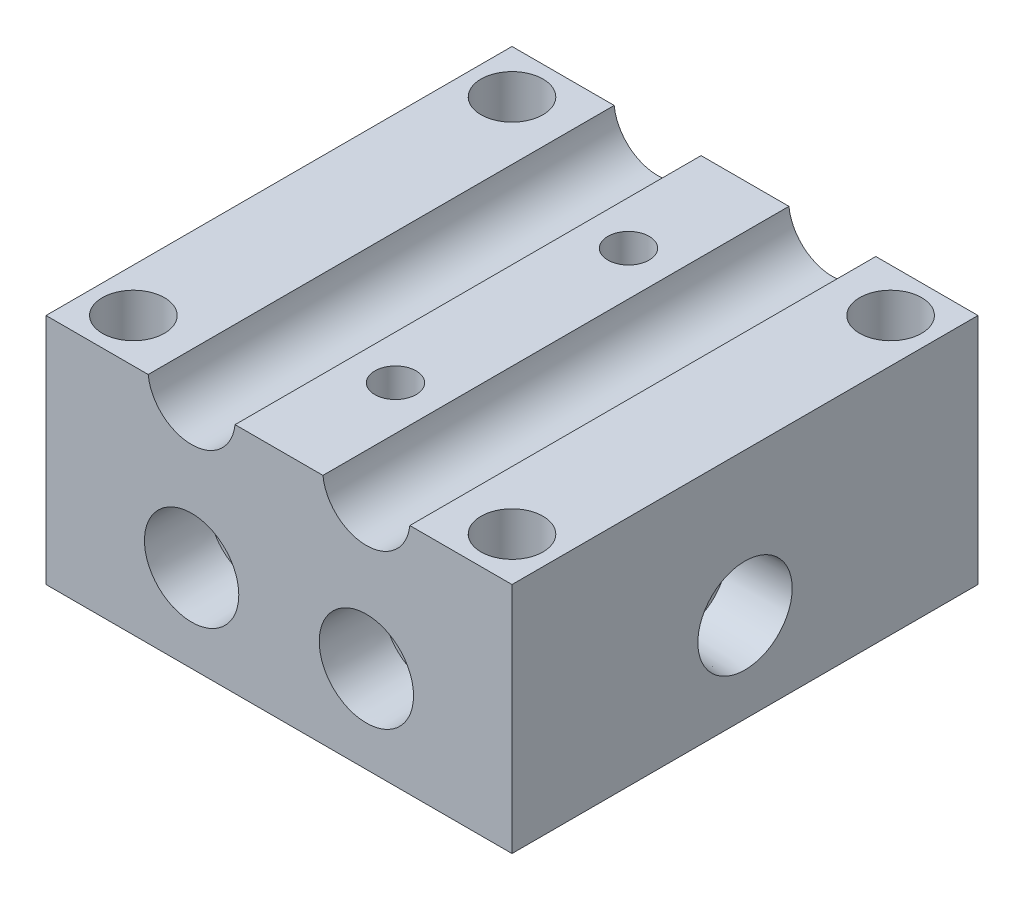
SolidWorks part; units mm, degrees
material "Copper"
ref_plane "Front Plane" through (0, 0, 0) normal (0, 0, 1) x (1, 0, 0)
ref_plane "Top Plane" through (0, 0, 0) normal (0, 1, 0) x (1, 0, 0)
ref_plane "Right Plane" through (0, 0, 0) normal (1, 0, 0) x (0, 0, -1)
sketch "Sketch1" plane through (0, 0, 0) normal (0, 1, 0) x (1, 0, 0)
  line L1 (25.4, 25.4) -> (-25.4, 25.4)
  line L2 (25.4, 25.4) -> (25.4, -25.4)
  line L3 (25.4, -25.4) -> (-25.4, -25.4)
  line L4 (-25.4, 25.4) -> (-25.4, -25.4)
  line L5 (25.4, 25.4) -> (-25.4, -25.4) construction
  line L6 (25.4, -25.4) -> (-25.4, 25.4) construction
  point P0 (0, 0)
  dimension "D1" = 50.8
  dimension "D2" = 50.8
extrude "Boss-Extrude1" add sketch "Sketch1" along normal blind 25.4
sketch "Sketch2" plane through (0, 0, 25.4) normal (0, 0, 1) x (1, 0, 0)
  circle A0 centre (-9.525, 25.908) radius 4.7625
  circle A1 centre (9.525, 25.908) radius 4.7625
  dimension "D1" = 9.525
  dimension "D2" = 19.05
extrude "Cut-Extrude1" cut sketch "Sketch2" against normal through all
hole_wizard "1/4 Clearance Hole1" positions "Sketch5" profile "Sketch4" hole size "1/4" standard "ANSI Inch" end condition through all
sketch "Sketch5" plane through (0, 25.4, 0) normal (0, 1, 0) x (1, 0, 0)
  point P0 (-20.6375, 20.6375)
  point P2 (-20.6375, -20.6375)
  point P4 (20.6375, -20.6375)
  point P6 (20.6375, 20.6375)
sketch "Sketch4" plane through (-20.6375, 25.4, -20.6375) normal (1, 0, 0) x (0, 0, 1)
  line L0 (0, 0) -> (0, 25.4)
  line L1 (0, 25.4) -> (3.3782, 25.4)
  line L2 (3.3782, 25.4) -> (3.3782, 0)
  line L5 (3.3782, 0) -> (0, 0)
  line L11 (0, -6.35) -> (0, 107.95) construction
  dimension "Thru Hole Dia." = 6.7564
  dimension "Thru Hole Depth" = 25.4
hole_wizard "#8 Clearance Hole1" positions "Sketch8" profile "Sketch7" hole size "#8" standard "ANSI Inch" end condition through all
sketch "Sketch8" plane through (0, 25.4, 0) normal (0, 1, 0) x (1, 0, 0)
  point P0 (0, 12.7)
  point P2 (0, -12.7)
sketch "Sketch7" plane through (0, 25.4, -12.7) normal (1, 0, 0) x (0, 0, 1)
  line L0 (0, 0) -> (0, 25.4)
  line L1 (0, 25.4) -> (2.2479, 25.4)
  line L2 (2.2479, 25.4) -> (2.2479, 0)
  line L5 (2.2479, 0) -> (0, 0)
  line L11 (0, -6.35) -> (0, 107.95) construction
  dimension "Thru Hole Dia." = 4.4958
  dimension "Thru Hole Depth" = 25.4
sketch "Sketch9" plane through (0, 0, 0) normal (0, -1, 0) x (1, 0, 0)
  circle A0 centre (0, 12.7) radius 4.445
  circle A1 centre (0, -12.7) radius 4.445
  dimension "D1" = 8.89
extrude "Cut-Extrude3" cut sketch "Sketch9" against normal blind 6.35
hole_wizard "1/8 NPT Tapped Hole1" positions "Sketch11" profile "Sketch10" size "1/8" standard "ANSI Inch"
sketch "Sketch11" plane through (0, 0, 25.4) normal (0, 0, 1) x (1, 0, 0)
  line L0 (-25.4, 0) -> (25.4, 0) construction
  line L1 (-25.4, 25.4) -> (-25.4, 0) construction
  point P0 (-9.525, 9.525)
  point P2 (9.525, 9.525)
  dimension "D1" = 9.525
  dimension "D2" = 15.875
  dimension "D3" = 19.05
sketch "Sketch10" plane through (-9.525, 9.525, 25.4) normal (1, 0, 0) x (0, -1, 0)
  line L0 (0, 0) -> (0, 46.9835)
  line L1 (4.2164, 44.45) -> (0, 46.9835)
  line L2 (-4.2164, 44.45) -> (0, 46.9835) construction
  line L3 (4.2164, 44.45) -> (4.2164, 6.858)
  line L4 (4.2164, 6.858) -> (4.9362, 6.858)
  line L5 (4.9362, 6.858) -> (5.1415, 0)
  line L6 (-4.9362, 6.858) -> (-5.1415, 0) construction
  line L7 (5.1415, 0) -> (0, 0)
  line L8 (0, -6.35) -> (0, 107.95) construction
  line L11 (-4.2164, 6.858) -> (-4.9362, 6.858) construction
  dimension "Tap Drill Dia." = 8.4328
  dimension "Tap Drill Depth" = 44.45
  dimension "Thread Dia." = 10.283
  dimension "Thread Angle" = 3.43
  dimension "Thread Depth" = 6.858
  dimension "Drill Angle" = 118
hole_wizard "1/8 NPT Tapped Hole3" positions "Sketch15" profile "Sketch14" size "1/8" standard "ANSI Inch"
sketch "Sketch15" plane through (25.4, 0, 0) normal (1, 0, 0) x (0, 0, -1)
  point P0 (0, 9.7793)
sketch "Sketch14" plane through (25.4, 9.7793, 0) normal (0, 1, 0) x (0, 0, -1)
  line L0 (0, 0) -> (0, 46.9835)
  line L1 (4.2164, 44.45) -> (0, 46.9835)
  line L2 (-4.2164, 44.45) -> (0, 46.9835) construction
  line L3 (4.2164, 44.45) -> (4.2164, 6.858)
  line L4 (4.2164, 6.858) -> (4.9362, 6.858)
  line L5 (4.9362, 6.858) -> (5.1415, 0)
  line L6 (-4.9362, 6.858) -> (-5.1415, 0) construction
  line L7 (5.1415, 0) -> (0, 0)
  line L8 (0, -6.35) -> (0, 107.95) construction
  line L11 (-4.2164, 6.858) -> (-4.9362, 6.858) construction
  dimension "Tap Drill Dia." = 8.4328
  dimension "Tap Drill Depth" = 44.45
  dimension "Thread Dia." = 10.283
  dimension "Thread Angle" = 3.43
  dimension "Thread Depth" = 6.858
  dimension "Drill Angle" = 118
